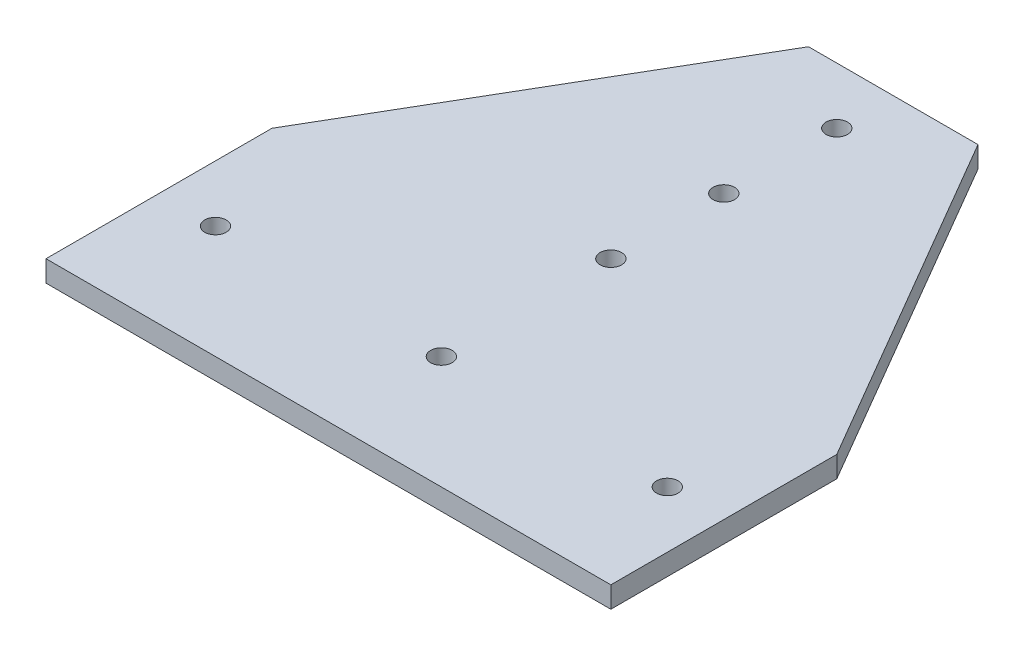
SolidWorks part; units mm, degrees
ref_plane "Front Plane" through (0, 0, 0) normal (0, 0, 1) x (1, 0, 0)
ref_plane "Top Plane" through (0, 0, 0) normal (0, 1, 0) x (1, 0, 0)
ref_plane "Right Plane" through (0, 0, 0) normal (1, 0, 0) x (0, 0, -1)
sketch "Sketch1" plane through (0, 0, 0) normal (0, 1, 0) x (1, 0, 0)
  line L0 (-63.5, -12.7) -> (-19.05, 63.5)
  line L1 (-63.5, 63.5) -> (63.5, 63.5)
  line L2 (-63.5, 63.5) -> (-63.5, -63.5)
  line L3 (-63.5, -63.5) -> (63.5, -63.5)
  line L4 (63.5, 63.5) -> (63.5, -63.5)
  line L5 (-63.5, 63.5) -> (63.5, -63.5) construction
  line L6 (-63.5, -63.5) -> (63.5, 63.5) construction
  line L7 (19.05, 63.5) -> (63.5, -12.7)
  circle A0 centre (0, -38.1) radius 2.413
  circle A1 centre (-50.8, -38.1) radius 2.413
  circle A2 centre (50.8, -38.1) radius 2.413
  circle A3 centre (0, 50.8) radius 2.413
  circle A5 centre (0, 0) radius 2.413
  circle A6 centre (0, 25.4) radius 2.413
  point P0 (0, 0)
  point P20 (0, 0)
  dimension "D8" = 4.826
  dimension "D9" = 4.826
  dimension "D10" = 4.826
  dimension "D14" = 4.826
  dimension "D13" = 4.826
  dimension "D16" = 4.826
  dimension "D1" = 127
  dimension "D2" = 127
  dimension "D3" = 50.8
  dimension "D4" = 50.8
  dimension "D5" = 38.1
  dimension "D6" = 19.05
  dimension "D7" = 25.4
  dimension "D11" = 12.7
  dimension "D12" = 12.7
  dimension "D15" = 12.7
  dimension "D17" = 25.4
extrude "Boss-Extrude1" add sketch "Sketch1" along normal blind 4.7625 contours L7 L1 L0 L2 L3 L4 A6 A5 A3 A2 A1 A0
